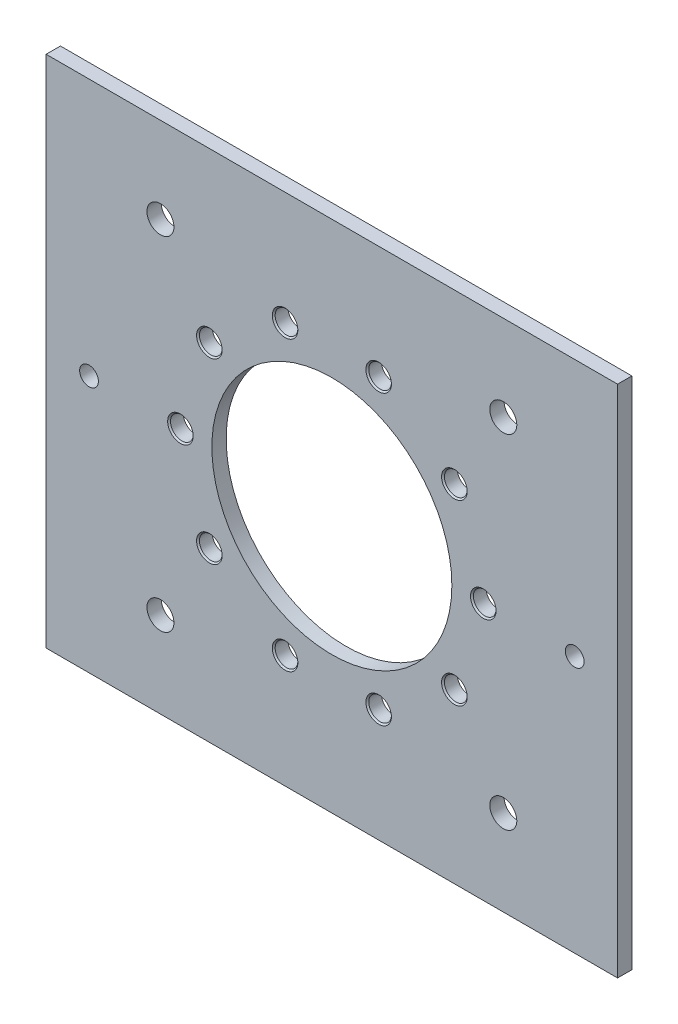
SolidWorks part; units mm, degrees
ref_plane "Front Plane" through (0, 0, 0) normal (0, 0, 1) x (1, 0, 0)
ref_plane "Top Plane" through (0, 0, 0) normal (0, 1, 0) x (1, 0, 0)
ref_plane "Right Plane" through (0, 0, 0) normal (1, 0, 0) x (0, 0, -1)
sketch "Sketch1" plane through (0, 0, 0) normal (0, 0, 1) x (1, 0, 0)
  line L1 (-127, -114.3) -> (127, -114.3)
  line L2 (-127, -114.3) -> (-127, 114.3)
  line L3 (-127, 114.3) -> (127, 114.3)
  line L4 (127, -114.3) -> (127, 114.3)
  line L5 (-127, -114.3) -> (127, 114.3) construction
  line L6 (-127, 114.3) -> (127, -114.3) construction
  circle A0 centre (0, 0) radius 53.34
  dimension "D1" = 127
  dimension "D3" = 106.68
  dimension "D2" = 114.3
extrude "Boss-Extrude1" add sketch "Sketch1" along normal blind 6.35
hole_wizard "3/8 Clearance Hole1" positions "Sketch5" profile "Sketch6" hole size "3/8" standard "ANSI Inch" end condition through all
sketch "Sketch5" plane through (0, 0, 6.35) normal (0, 0, 1) x (1, 0, 0)
  circle A0 centre (0, 0) radius 67.31
  point P10 (-67.31, 0)
  point P18 (-54.4549, 39.5638)
  point P19 (-20.7999, 64.0156)
  point P20 (20.7999, 64.0156)
  point P21 (54.4549, 39.5638)
  point P22 (67.31, 0)
  point P23 (54.4549, -39.5638)
  point P24 (20.7999, -64.0156)
  point P25 (-20.7999, -64.0156)
  point P26 (-54.4549, -39.5638)
  dimension "D1" = 134.62
  dimension "D2" = 10
sketch "Sketch6" plane through (-54.4549, -39.5638, 6.35) normal (1, 0, 0) x (0, -1, 0)
  line L0 (0, 0) -> (0, 6.35)
  line L1 (0, 6.35) -> (5.0419, 6.35)
  line L2 (5.0419, 6.35) -> (5.0419, 0.635)
  line L3 (5.0419, 0.635) -> (5.6769, 0)
  line L5 (5.6769, 0) -> (0, 0)
  line L6 (-5.0419, 0.635) -> (-5.6769, 0) construction
  line L11 (0, -6.35) -> (0, 107.95) construction
  dimension "Thru Hole Dia." = 10.0838
  dimension "Thru Hole Depth" = 6.35
  dimension "Near C'Sink Dia." = 11.3538
  dimension "Near C'Sink Angle" = 90
hole_wizard "Ø12.0 (12) Diameter Hole1" positions "Sketch8" profile "Sketch10" hole size "Ø12.0" standard "ANSI Metric" end condition through all
sketch "Sketch8" plane through (0, 0, 0) normal (0, 0, -1) x (-1, 0, 0)
  line L0 (127, 0) -> (-127, 0) construction
  line L1 (127, 114.3) -> (127, -114.3) construction
  line L2 (-127, -114.3) -> (-127, 114.3) construction
  line L4 (0, 114.3) -> (0, -114.3) construction
  line L5 (-127, 114.3) -> (127, 114.3) construction
  line L6 (127, -114.3) -> (-127, -114.3) construction
  point P9 (76.2, 76.2)
  point P30 (76.2, -76.2)
  point P31 (-76.2, -76.2)
  point P32 (-76.2, 76.2)
  dimension "D1" = 76.2
  dimension "D2" = 76.2
sketch "Sketch10" plane through (-76.2, 76.2, 0) normal (1, 0, 0) x (0, 1, 0)
  line L0 (0, 0) -> (0, 6.35)
  line L1 (0, 6.35) -> (6, 6.35)
  line L2 (6, 6.35) -> (6, 0)
  line L5 (6, 0) -> (0, 0)
  line L11 (0, -6.35) -> (0, 107.95) construction
  dimension "Thru Hole Dia." = 12
  dimension "Thru Hole Depth" = 6.35
sketch "Sketch11" plane through (0, 0, 0) normal (0, 0, -1) x (-1, 0, 0)
  line L0 (127, 114.3) -> (127, -114.3) construction
  line L1 (127, 114.3) -> (127, -114.3) construction
  line L2 (127, 0) -> (-127, 0) construction
  line L3 (-127, -114.3) -> (-127, 114.3) construction
  circle A0 centre (107.95, 0) radius 4.1656
  circle A1 centre (-107.95, 0) radius 4.1656
  point P10 (0, 0)
  dimension "D1" = 8.3312
  dimension "D2" = 19.05
  dimension "D3" = 19.05
extrude "Cut-Extrude1" cut sketch "Sketch11" against normal through all
sketch "Sketch12" [suppressed] plane through (0, 0, 6.35) normal (0, 0, 1) x (1, 0, 0)
  line L0 (127, 76.2) -> (-127, 76.2) construction
  line L1 (101.6, -76.2) -> (-101.6, -76.2)
  line L2 (101.6, -76.2) -> (101.6, 76.2)
  line L3 (101.6, 76.2) -> (-101.6, 76.2)
  line L4 (-101.6, -76.2) -> (-101.6, 76.2)
  line L5 (101.6, -76.2) -> (-101.6, 76.2) construction
  line L6 (101.6, 76.2) -> (-101.6, -76.2) construction
  line L7 (-127, 76.2) -> (-127, -76.2) construction
  point P0 (0, 0)
  dimension "D1" = 25.4
extrude "Cut-Extrude2" [suppressed] cut sketch "Sketch12" against normal through all flip side to cut
sketch "Sketch13" [suppressed] plane through (0, 0, 6.35) normal (0, 0, 1) x (1, 0, 0)
  circle A0 centre (0, 0) radius 53.34 construction
  circle A1 centre (0, 0) radius 53.34
extrude "Boss-Extrude2" [suppressed] add sketch "Sketch13" against normal blind 6.35
hole_wizard "3/4 Clearance Hole1" [suppressed] positions "Sketch14" profile "Sketch15" hole size "3/4" standard "ANSI Inch"
sketch "Sketch14" plane through (0, 0, 6.35) normal (0, 0, 1) x (1, 0, 0)
  point P0 (0, 0)
sketch "Sketch15" plane through (0, 0, 6.35) normal (1, 0, 0) x (0, -1, 0)
  line L0 (0, 0) -> (0, 6.35)
  line L1 (0, 6.35) -> (9.9212, 6.35)
  line L2 (9.9212, 6.35) -> (9.9212, 0)
  line L5 (9.9212, 0) -> (0, 0)
  line L11 (0, -6.35) -> (0, 107.95) construction
  dimension "Thru Hole Dia." = 19.8425
  dimension "Thru Hole Depth" = 6.35
sketch "Sketch16" [suppressed] plane through (0, 0, 6.35) normal (0, 0, 1) x (1, 0, 0)
  circle A1 centre (0, 0) radius 63.5
  dimension "D1" = 127
extrude "Cut-Extrude3" [suppressed] cut sketch "Sketch16" against normal blind 6.35
sketch "Sketch17" [suppressed] plane through (0, 0, 6.35) normal (0, 0, 1) x (1, 0, 0)
  line L0 (0, 139.7) -> (0, -139.7) construction
  line L1 (-139.7, 139.7) -> (-146.05, 139.7)
  line L2 (-139.7, 139.7) -> (-139.7, -76.2)
  line L3 (-139.7, -76.2) -> (-146.05, -76.2)
  line L4 (-146.05, 139.7) -> (-146.05, -76.2)
  line L5 (139.7, 139.7) -> (-139.7, 139.7) construction
  line L6 (-139.7, -139.7) -> (139.7, -139.7) construction
  line L7 (139.7, -76.2) -> (146.05, -76.2)
  line L8 (146.05, 139.7) -> (146.05, -76.2)
  line L9 (139.7, 139.7) -> (146.05, 139.7)
  line L10 (139.7, 139.7) -> (139.7, -76.2)
  dimension "D1" = 6.35
extrude "Boss-Extrude3" [suppressed] add sketch "Sketch17" against normal blind 12.7
sketch "Sketch18" [suppressed] plane through (0, 0, 6.35) normal (0, 0, 1) x (1, 0, 0)
  line L0 (-146.05, 25.4) -> (146.05, 25.4) construction
  line L1 (-146.05, 127) -> (-146.05, -76.2) construction
  line L2 (146.05, -76.2) -> (146.05, 127) construction
  line L3 (0, 127) -> (0, -127) construction
  line L4 (146.05, 127) -> (-146.05, 127) construction
  line L5 (-139.7, -127) -> (139.7, -127) construction
  circle A0 centre (-127, 25.4) radius 4.1656
  circle A1 centre (127, 25.4) radius 4.1656
  dimension "D1" = 8.3312
  dimension "D2" = 19.05
extrude "Cut-Extrude4" [suppressed] cut sketch "Sketch18" against normal through all
sketch "Sketch21" [suppressed] plane through (0, 0, 6.35) normal (0, 0, 1) x (1, 0, 0)
  line L12 (127, -76.2) -> (127, 76.2) construction
  line L13 (-127, -76.2) -> (127, -76.2) construction
  line L14 (-127, 76.2) -> (-127, -76.2) construction
  line L15 (127, 76.2) -> (-127, 76.2) construction
  line L20 (-215.9, -127) -> (215.9, -127)
  line L21 (215.9, -127) -> (215.9, 152.4)
  line L22 (-215.9, 152.4) -> (-215.9, -127)
  line L23 (215.9, 152.4) -> (-215.9, 152.4)
  line L24 (127, -76.2) -> (127, 76.2)
  line L25 (-127, -76.2) -> (127, -76.2)
  line L26 (-127, 76.2) -> (-127, -76.2)
  line L27 (127, 76.2) -> (-127, 76.2)
  dimension "D1" = 88.9
  dimension "D2" = 88.9
  dimension "D3" = 50.8
  dimension "D4" = 76.2
extrude "Boss-Extrude5" [suppressed] add sketch "Sketch21" against normal blind 6.35
sketch "Sketch19" [suppressed] plane through (0, 0, 6.35) normal (0, 0, 1) x (1, 0, 0)
  line L0 (0, 152.4) -> (0, -127) construction
  line L3 (-25.4, 152.4) -> (-25.4, -127) construction
  line L5 (215.9, 152.4) -> (-215.9, 152.4) construction
  line L6 (-215.9, -127) -> (215.9, -127) construction
  circle A0 centre (-25.4, 127) radius 6.35
  circle A1 centre (-25.4, 25.4) radius 6.35
  circle A2 centre (25.4, 25.4) radius 6.35
  circle A3 centre (25.4, 127) radius 6.35
  circle A4 centre (-25.4, -76.2) radius 6.35
  circle A5 centre (25.4, -76.2) radius 6.35
  dimension "D2" = 12.7
  dimension "D1" = 25.4
  dimension "D3" = 2
  dimension "D5" = 101.6
  dimension "D6" = 101.6
  dimension "D7" = 25.4
  dimension "D4" = 2
extrude "Cut-Extrude5" [suppressed] cut sketch "Sketch19" against normal through all
sketch "Sketch22" [suppressed] plane through (0, 0, 6.35) normal (0, 0, 1) x (1, 0, 0)
  line L0 (-27.94, 109.855) -> (27.94, 109.855) construction
  line L1 (0, 109.855) -> (-84.1538, -70.6134) construction
  line L2 (-84.1538, -70.6134) -> (84.1538, -70.6134) construction
  line L3 (84.1538, -70.6134) -> (0, 109.855) construction
  line L4 (-102.1133, -49.2102) -> (-66.1943, -92.0167) construction
  line L5 (0, 109.855) -> (0, -139.7) construction
  line L6 (-139.7, -139.7) -> (139.7, -139.7) construction
  line L7 (102.1133, -49.2102) -> (66.1943, -92.0167) construction
  circle A0 centre (0, 0) radius 109.855 construction
  point P5 (0, 109.855)
  point P11 (-84.1538, -70.6134)
  dimension "D1" = 219.71
  dimension "D2" = 55.88
  dimension "D3" = 65
  dimension "D4" = 55.88
hole_wizard "#8 Clearance Hole1" [suppressed] positions "3DSketch1" profile "Sketch23" hole size "#8" standard "ANSI Inch"
sketch3d "3DSketch1"
  point P0 (-27.94, 109.855, 6.35)
  point P3 (27.94, 109.855, 6.35)
  point P6 (102.1133, -49.2102, 6.35)
  point P9 (66.1943, -92.0167, 6.35)
  point P12 (-66.1943, -92.0167, 6.35)
  point P15 (-102.1133, -49.2102, 6.35)
sketch "Sketch23" plane through (-27.94, 109.855, 6.35) normal (1, 0, 0) x (0, -1, 0)
  line L0 (0, 0) -> (0, 13.97)
  line L1 (0, 13.97) -> (2.2479, 12.6193)
  line L2 (2.2479, 12.6193) -> (2.2479, 0)
  line L5 (2.2479, 0) -> (0, 0)
  line L10 (0, 13.97) -> (-2.2479, 12.6193) construction
  line L11 (0, -6.35) -> (0, 107.95) construction
  dimension "Hole Dia." = 4.4958
  dimension "Hole Depth" = 13.97
  dimension "Drill Angle" = 118
